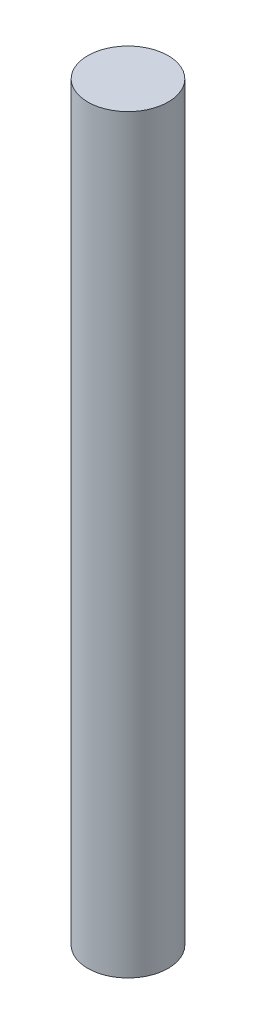
SolidWorks part; units mm, degrees
ref_plane "Front Plane" through (0, 0, 0) normal (0, 0, 1) x (1, 0, 0)
ref_plane "Top Plane" through (0, 0, 0) normal (0, 1, 0) x (1, 0, 0)
ref_plane "Right Plane" through (0, 0, 0) normal (1, 0, 0) x (0, 0, -1)
sketch "Sketch1" plane through (0, 0, 0) normal (0, 1, 0) x (1, 0, 0)
  circle A0 centre (0, 0) radius 1.5
  dimension "D1" = 1.5
extrude "Boss-Extrude1" add sketch "Sketch1" along normal blind 28
equation "\"N_pins\"= 26"
equation "\"N_lobes\"= \"N_pins\" - 1"
equation "\"R_pc\"= 25"
equation "\"D_pin\"= 3"
equation "\"R_pin\"= \"D_pin\" / 2"
equation "\"ecc\"= 0.72"
equation "\"t_disc\"= 7"
equation "\"N_out\"= 8"
equation "\"D_outc\"=22"
equation "\"D_roller\"= 5"
equation "\"D_outhole\"= \"D_roller\" + 2 * \"ecc\""
equation "\"D_cam_OD\"= 21"
equation "\"D_cam_ID\"= 10"
equation "\"clr_bore\"= 1"
equation "\"D_bore\"= 2 * \"R_pc\" + \"clr_bore\""
equation "\"t_wall\"= 7.5"
equation "\"D_housing\"= \"D_bore\" + 2 * \"t_wall\""
equation "\"D1@Sketch1\"=\"R_pin\""
